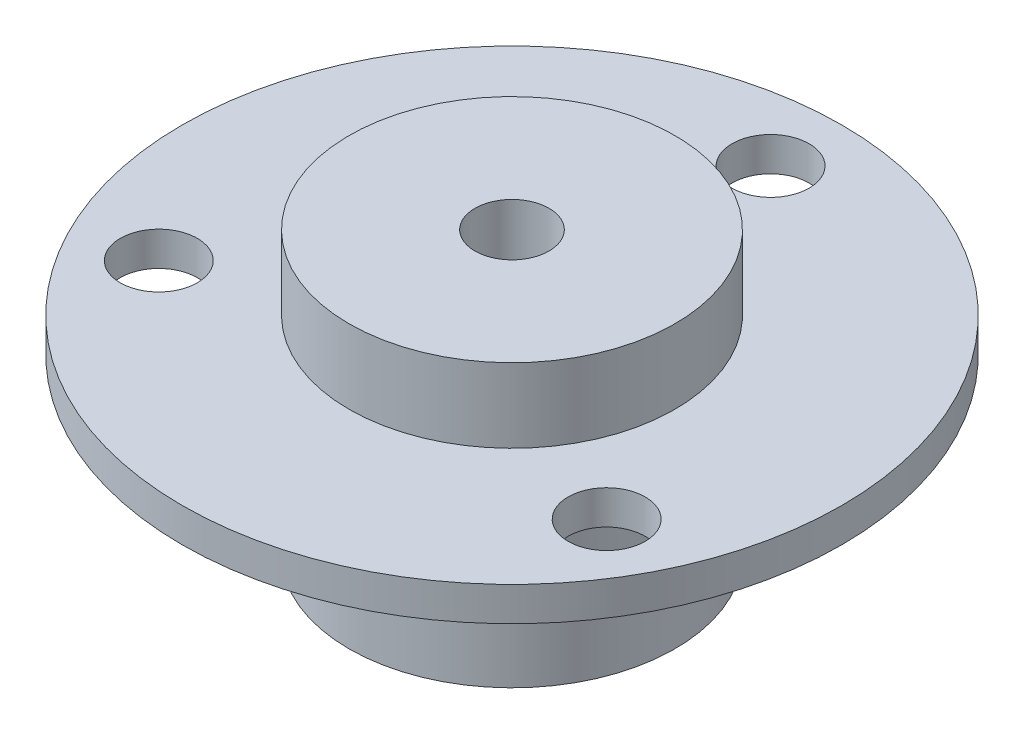
SolidWorks part; units mm, degrees
ref_plane "前视基准面" through (0, 0, 0) normal (0, 0, 1) x (1, 0, 0)
ref_plane "上视基准面" through (0, 0, 0) normal (0, 1, 0) x (1, 0, 0)
ref_plane "右视基准面" through (0, 0, 0) normal (1, 0, 0) x (0, 0, -1)
sketch "草图1" plane through (0, 0, 0) normal (0, 1, 0) x (1, 0, 0)
  circle A0 centre (0, 0) radius 11
  dimension "D1" = 22
extrude "凸台-拉伸1" add sketch "草图1" against normal blind 19
ref_plane "基准面1" through (0, -5, 0) normal (0, 1, 0) x (1, 0, 0)
sketch "草图2" plane through (0, -5, 0) normal (0, 1, 0) x (1, 0, 0)
  circle A0 centre (0, 0) radius 22.25
  dimension "D1" = 44.5
extrude "凸台-拉伸2" add sketch "草图2" against normal blind 2.3
sketch "草图3" plane through (0, -5, 0) normal (0, 1, 0) x (1, 0, 0)
  circle A0 centre (0, 0) radius 17.45 construction
  circle A1 centre (0, 17.45) radius 2.6
  circle A2 centre (15.1121, -8.725) radius 2.6
  circle A3 centre (-15.1121, -8.725) radius 2.6
  point P11 (0, 0)
  dimension "D1" = 34.9
  dimension "D2" = 5.2
  dimension "D3" = 3
extrude "切除-拉伸1" cut sketch "草图3" against normal through all
sketch "草图4" plane through (0, 0, 0) normal (0, 1, 0) x (1, 0, 0)
  circle A0 centre (0, 0) radius 2.5
  dimension "D1" = 5
extrude "切除-拉伸2" cut sketch "草图4" against normal through all
